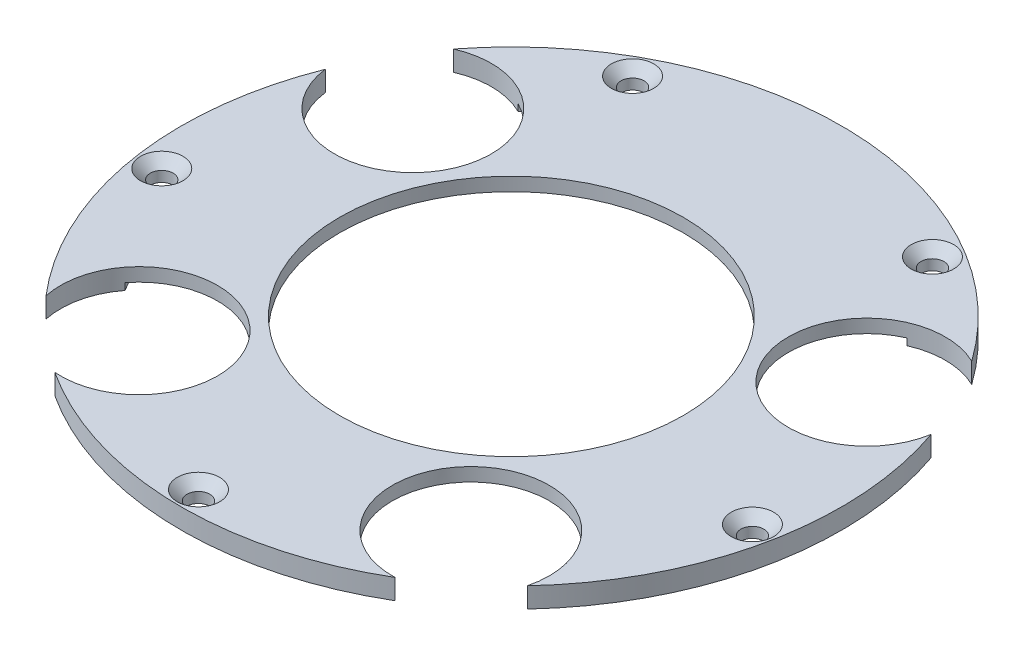
SolidWorks part; units mm, degrees
material "6061 Alloy"
ref_plane "Front Plane" through (0, 0, 0) normal (0, 0, 1) x (1, 0, 0)
ref_plane "Top Plane" through (0, 0, 0) normal (0, 1, 0) x (1, 0, 0)
ref_plane "Right Plane" through (0, 0, 0) normal (1, 0, 0) x (0, 0, -1)
sketch "Sketch1" plane through (0, 0, 0) normal (0, 1, 0) x (-1, 0, 0)
  circle A0 centre (-29.3916, 2.6114) radius 25.506
  arc A1 (-61.273, -25.5499) -> (1.258, -26.8859) centre (-29.3916, 2.6114) ccw
  arc A2 (-63.3517, 28.2276) -> (-47.0557, 41.3084) centre (-53.9124, 33.1593) ccw
  arc A3 (-10.0908, 40.5186) -> (5.6317, 26.7537) centre (-3.5884, 32.0841) ccw
  arc A4 (11.6063, -8.7315) -> (1.258, -26.8859) centre (4.64, -16.7871) ccw
  arc A5 (-61.273, -25.5499) -> (-70.8364, -6.97) centre (-64.2206, -15.3159) ccw
  arc A6 (11.6063, -8.7315) -> (5.6317, 26.7537) centre (-29.3916, 2.6114) ccw
  arc A7 (-10.0908, 40.5186) -> (-47.0557, 41.3084) centre (-29.3916, 2.6114) ccw
  arc A8 (-63.3517, 28.2276) -> (-70.8364, -6.97) centre (-29.3916, 2.6114) ccw
  dimension "D1" = 51.012
extrude "Boss-Extrude1" add sketch "Sketch1" along normal blind 2
sketch "Sketch2" plane through (0, 2, 0) normal (0, 1, 0) x (1, 0, 0)
  arc A0 (8.1008, -41.7309) -> (10.9147, -39.8137) centre (3.5884, -32.0841) ccw
  arc A1 (64.1983, -30.3985) -> (62.8013, -27.2933) centre (53.9124, -33.1593) ccw
  arc A2 (63.5693, 25.9459) -> (60.2476, 25.1971) centre (64.2206, 15.3159) ccw
  arc A3 (-0.2486, 26.4896) -> (-3.5352, 27.3797) centre (-4.64, 16.7871) ccw
  arc A4 (-5.0419, -25.8438) -> (-6.5703, -28.8865) centre (3.5884, -32.0841) ccw
  arc A5 (62.8013, -27.2933) -> (69.9535, 6.3406) centre (29.3916, -2.6114) ccw
  arc A6 (46.2626, -40.5689) -> (48.9921, -42.6045) centre (53.9124, -33.1593) ccw
  arc A7 (60.2476, 25.1971) -> (-0.2486, 26.4896) centre (29.3916, -2.6114) ccw
  arc A8 (8.1008, -41.7309) -> (48.9921, -42.6045) centre (29.3916, -2.6114) ccw
  arc A9 (69.9535, 6.3406) -> (72.4931, 8.6086) centre (64.2206, 15.3159) ccw
  arc A10 (64.1983, -30.3985) -> (72.4931, 8.6086) centre (29.3916, -2.6114) ccw
  arc A11 (-13.1914, 10.4393) -> (-6.5703, -28.8865) centre (29.3916, -2.6114) ccw
  arc A12 (63.5693, 25.9459) -> (-3.5352, 27.3797) centre (29.3916, -2.6114) ccw
  arc A13 (-10.751, 8.0648) -> (-5.0419, -25.8438) centre (29.3916, -2.6114) ccw
  arc A14 (-13.1914, 10.4393) -> (-10.751, 8.0648) centre (-4.64, 16.7871) ccw
  arc A17 (10.9147, -39.8137) -> (46.2626, -40.5689) centre (29.3916, -2.6114) ccw
extrude "Boss-Extrude2" add sketch "Sketch2" against normal blind 3
sketch "Sketch3" plane through (0, 2, 0) normal (0, 1, 0) x (1, 0, 0)
  line L0 (29.3916, -2.6114) -> (54.9375, 33.872)
  line L1 (29.3916, -2.6114) -> (69.7567, -21.4339)
  line L2 (29.3916, -2.6114) -> (37.9488, 15.7396) construction
  line L3 (29.3916, -2.6114) -> (7.7452, 12.5456) construction
  line L4 (29.3916, -2.6114) -> (29.3916, 10.2436)
  line L5 (29.3916, -2.6114) -> (3.8456, 33.872)
  line L6 (29.3916, -2.6114) -> (-10.9736, -21.4339)
  line L7 (29.3916, -2.6114) -> (39.4769, -24.2395) construction
  line L8 (29.3916, -2.6114) -> (11.5965, -15.0716) construction
  arc A0 (63.5693, 25.9459) -> (-3.5352, 27.3797) centre (29.3916, -2.6114) ccw construction
  arc A1 (64.1983, -30.3985) -> (72.4931, 8.6086) centre (29.3916, -2.6114) ccw construction
ref_plane "Plane1" through (25.1423, 0, 11.724) normal (0.9063, 0, 0.4226) x (0.4226, 0, -0.9063)
ref_plane "Plane2" through (8.4426, 0, -12.0573) normal (0.5736, 0, -0.8192) x (-0.8192, 0, -0.5736)
sketch "Sketch7" plane through (0, 2, 0) normal (0, 1, 0) x (1, 0, 0)
  line L0 (29.3916, 41.9266) -> (29.3916, -47.1494) construction
  arc A0 (63.5693, 25.9459) -> (-3.5352, 27.3797) centre (29.3916, -2.6114) ccw construction
  arc A1 (8.1008, -41.7309) -> (48.9921, -42.6045) centre (29.3916, -2.6114) ccw construction
sketch "Sketch8" plane through (0, -1, 0) normal (0, -1, 0) x (1, 0, 0)
  line L0 (29.3916, 47.1494) -> (29.3916, -41.9266) construction
ref_plane "Plane3" through (29.3916, 0, 0) normal (1, 0, 0) x (0, 0, -1)
extrude "Cut-Extrude13" cut sketch "Sketch20" along normal through all
sketch "Sketch20" plane through (20.602, -45.3917, -3.5432) normal (0.5736, 0, -0.8192) x (-0.8192, 0, -0.5736)
  circle A0 centre (-10.7301, 42.3917) radius 2
extrude "Cut-Extrude14" cut sketch "Sketch21" against normal through all
sketch "Sketch21" plane through (30.9387, -45.3917, 1.5281) normal (0.5736, 0, 0.8192) x (0.8192, 0, -0.5736)
  circle A0 centre (-1.8886, 42.3917) radius 2
extrude "Cut-Extrude15" cut sketch "Sketch22" along normal through all
sketch "Sketch22" plane through (24.2144, -45.3917, -8.4911) normal (-0.9063, 0, 0.4226) x (0.4226, 0, 0.9063)
  circle A0 centre (12.2353, 42.3917) radius 2
sketch "Sketch24" plane through (0, 2, 0) normal (0, 1, 0) x (1, 0, 0)
  arc A0 (-15.2615, 17.5655) -> (-13.1914, 10.4393) centre (-4.64, 16.7871) ccw
  circle A1 centre (29.3916, -2.6114) radius 49
  arc A2 (70.67, 23.7911) -> (63.5692, 25.946) centre (64.2206, 15.3159) ccw
  arc A3 (0.7048, -42.3363) -> (8.1008, -41.7309) centre (3.5884, -32.0841) ccw
  arc A4 (63.5045, -37.7867) -> (64.1983, -30.3985) centre (53.9124, -33.1593) ccw
  arc A5 (-13.1914, 10.4393) -> (-6.5703, -28.8865) centre (29.3916, -2.6114) ccw
  arc A6 (-3.5352, 27.3797) -> (-10.7217, 25.5298) centre (-4.64, 16.7871) ccw
  arc A7 (72.4932, 8.6085) -> (74.8658, 15.6395) centre (64.2206, 15.3159) ccw
  arc A8 (63.5692, 25.946) -> (-3.5352, 27.3797) centre (29.3916, -2.6114) ccw
  arc A9 (48.9921, -42.6045) -> (56.3555, -43.5253) centre (53.9124, -33.1593) ccw
  arc A10 (64.1983, -30.3985) -> (72.4932, 8.6085) centre (29.3916, -2.6114) ccw
  arc A11 (-6.5703, -28.8865) -> (-6.1927, -36.2976) centre (3.5884, -32.0841) ccw
  arc A12 (8.1008, -41.7309) -> (48.9921, -42.6045) centre (29.3916, -2.6114) ccw
  arc M2 (-13.1914, 10.4393) -> (-6.5703, -28.8865) centre (29.3916, -2.6114) ccw
  arc M4 (8.1008, -41.7309) -> (48.9921, -42.6045) centre (29.3916, -2.6114) ccw
  arc M6 (64.1983, -30.3985) -> (72.4931, 8.6086) centre (29.3916, -2.6114) ccw
  arc M8 (63.5693, 25.9459) -> (-3.5352, 27.3797) centre (29.3916, -2.6114) ccw
extrude "Boss-Extrude6" add sketch "Sketch24" against normal blind 3 contours A6 A2 A1 M8 | A11 A0 A1 M2 | A7 A4 A1 M6 | A9 A3 A1 M4
extrude "Cut-Extrude16" cut sketch "Sketch25" against normal through all
sketch "Sketch25" plane through (0.0625, 2, -0.6272) normal (0, 1, 0) x (-0.9998, 0, -0.0214)
  line L0 (-29.3916, 2.6114) -> (-29.3916, 48.1114) construction
  line L1 (-29.3916, 2.6114) -> (-52.1416, -36.7928) construction
  line L2 (-29.3916, 2.6114) -> (-74.2003, 10.5124) construction
  line L3 (-29.3916, 2.6114) -> (-6.6416, -36.7928) construction
  line L4 (-29.3916, 2.6114) -> (15.4172, 10.5124) construction
  circle A0 centre (-29.3916, 48.1114) radius 1.7
  circle A1 centre (-74.2003, 10.5124) radius 1.7
  circle A2 centre (-52.1416, -36.7928) radius 1.7
  circle A3 centre (-6.6416, -36.7928) radius 1.7
  circle A4 centre (15.4172, 10.5124) radius 1.7
sketch "Sketch31" plane through (0, 2, 0) normal (0, 1, 0) x (1, 0, 0)
  point P0 (7.4885, 37.2698)
  point P1 (52.9781, 36.2978)
  point P3 (74.0213, -11.4677)
  point P5 (-15.5757, -9.5534)
  point P7 (28.4197, -48.101)
hole_wizard "CSK for M3 Flat Head Machine Screw1" positions "Sketch36" profile "Sketch35" countersink size "M3" standard "Ansi Metric" end condition through all
sketch "Sketch36" plane through (0, 2, 0) normal (0, 1, 0) x (-1, 0, 0)
  point P2 (-7.4885, -37.2698)
  point P5 (-52.9781, -36.2978)
  point P8 (-74.0213, 11.4677)
  point P11 (-28.4197, 48.101)
  point P14 (15.5757, 9.5534)
sketch "Sketch35" plane through (7.4885, 2, -37.2698) normal (1, 0, 0) x (0, 0, 1)
  line L0 (0, 0) -> (0, 3)
  line L1 (0, 3) -> (1.7, 3)
  line L2 (1.7, 3) -> (1.7, 1.45)
  line L3 (1.7, 1.45) -> (3.15, 0)
  line L5 (3.15, 0) -> (0, 0)
  line L6 (-1.7, 1.45) -> (-3.15, 0) construction
  line L11 (0, -6.35) -> (0, 107.95) construction
  dimension "Thru Hole Dia." = 3.4
  dimension "Thru Hole Depth" = 3
  dimension "Near C'Sink Dia." = 6.3
  dimension "Near C'Sink Angle" = 90
sketch "Sketch38" plane through (0, 2, 0) normal (0, 1, 0) x (1, 0, 0)
  circle A0 centre (-4.64, 16.7871) radius 10.65
  circle A1 centre (64.2206, 15.3159) radius 10.65
  circle A2 centre (53.9124, -33.1593) radius 10.65
  circle A3 centre (3.5884, -32.0841) radius 10.65
  circle A4 centre (-4.64, 16.7871) radius 11.65
  circle A5 centre (64.2206, 15.3159) radius 11.65
  circle A6 centre (53.9124, -33.1593) radius 11.65
  circle A7 centre (3.5884, -32.0841) radius 11.65
  dimension "D1" = 1
extrude "Cut-Extrude18" cut sketch "Sketch38" against normal blind 10
